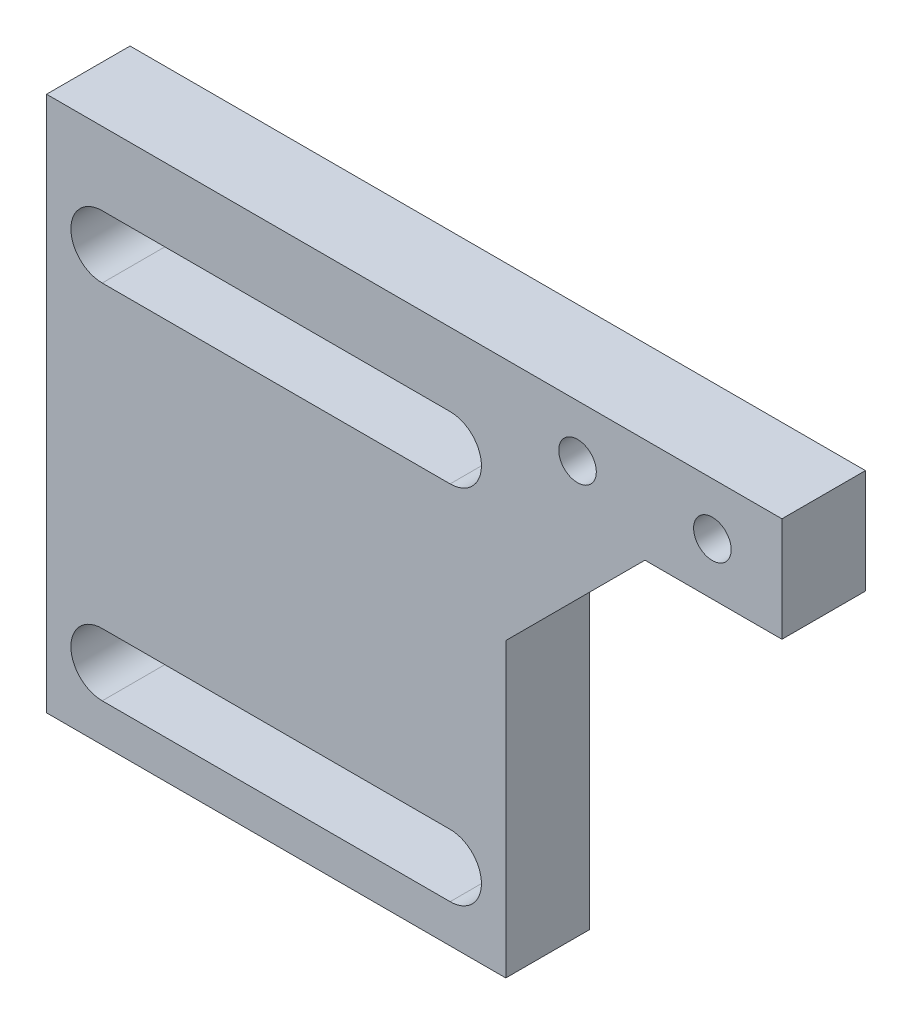
SolidWorks part; units mm, degrees
ref_plane "Front Plane" through (0, 0, 0) normal (0, 0, 1) x (1, 0, 0)
ref_plane "Top Plane" through (0, 0, 0) normal (0, 1, 0) x (1, 0, 0)
ref_plane "Right Plane" through (0, 0, 0) normal (1, 0, 0) x (0, 0, -1)
sketch "Sketch7" plane through (0, 0, 0) normal (0, 0, 1) x (1, 0, 0)
  line L0 (-52.845, 0) -> (0, 0)
  line L2 (0, 0) -> (0, -7.5)
  line L3 (0, -7.5) -> (-19.845, -7.5)
  line L6 (-19.845, -7.5) -> (-19.845, -38.5)
  line L7 (-19.845, -38.5) -> (-52.845, -38.5)
  line L8 (-52.845, 0) -> (-52.845, -38.5)
  line L9 (-14.69, -3.75) -> (-5, -3.75) construction
  line L10 (-48.845, -7.5) -> (-23.845, -7.5) construction
  line L11 (-48.845, -5.25) -> (-23.845, -5.25)
  line L12 (-48.845, -9.75) -> (-23.845, -9.75)
  line L13 (-48.845, -33.5) -> (-23.845, -33.5) construction
  line L14 (-48.845, -31.25) -> (-23.845, -31.25)
  line L15 (-48.845, -35.75) -> (-23.845, -35.75)
  circle A0 centre (-14.69, -3.75) radius 1.35
  circle A1 centre (-5, -3.75) radius 1.35
  arc A2 (-48.845, -5.25) -> (-48.845, -9.75) centre (-48.845, -7.5) ccw
  arc A3 (-23.845, -9.75) -> (-23.845, -5.25) centre (-23.845, -7.5) ccw
  arc A4 (-48.845, -31.25) -> (-48.845, -35.75) centre (-48.845, -33.5) ccw
  arc A5 (-23.845, -35.75) -> (-23.845, -31.25) centre (-23.845, -33.5) ccw
  point P11 (-9.845, -3.75)
  point P12 (-36.345, -11.1093)
  point P13 (0, -3.75)
  point P16 (-36.345, -7.5)
  point P23 (-36.345, -33.5)
  point P28 (0, 0)
  dimension "D3" = 2.7
  dimension "D2" = 9.69
  dimension "D4" = 5
  dimension "D5" = 4.5
  dimension "D6" = 25
  dimension "D7" = 25
  dimension "D8" = 26
  dimension "D9" = 4
  dimension "D10" = 4
  dimension "D11" = 5
  dimension "D12" = 7.5
  dimension "D13" = 10
extrude "Boss-Extrude4" add sketch "Sketch7" along normal blind 6
chamfer "Chamfer1" distance 10 angle 45 1 edges at (-19.845, -7.5, 3)
